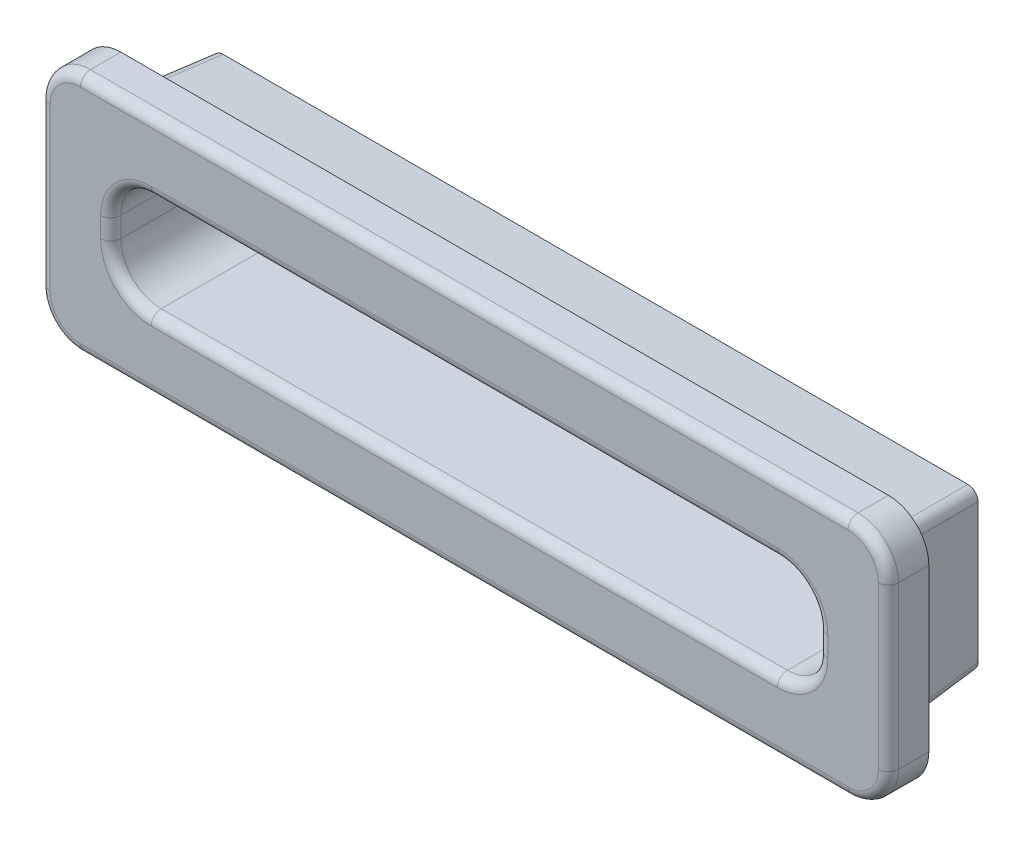
SolidWorks part; units mm, degrees
ref_plane "Front Plane" through (0, 0, 0) normal (0, 0, 1) x (1, 0, 0)
ref_plane "Top Plane" through (0, 0, 0) normal (0, 1, 0) x (1, 0, 0)
ref_plane "Right Plane" through (0, 0, 0) normal (1, 0, 0) x (0, 0, -1)
sketch "Sketch2" plane through (0, 0, 0) normal (0, 0, 1) x (1, 0, 0)
  line L1 (-35, 5) -> (35, 5)
  line L2 (-35, 5) -> (-35, -5)
  line L3 (-35, -5) -> (35, -5)
  line L4 (35, 5) -> (35, -5)
  line L5 (-35, 5) -> (35, -5) construction
  line L6 (-35, -5) -> (35, 5) construction
  line L7 (-42, 12) -> (42, 12)
  line L8 (-42, 12) -> (-42, -12)
  line L9 (-42, -12) -> (42, -12)
  line L10 (42, 12) -> (42, -12)
  line L11 (-42, 12) -> (42, -12) construction
  line L12 (-42, -12) -> (42, 12) construction
  point P0 (0, 0)
  point P5 (0, 0)
  dimension "D1" = 10
  dimension "D2" = 70
  dimension "D3" = 7
  dimension "D4" = 7
extrude "Boss-Extrude1" add sketch "Sketch2" along normal blind 4
sketch "Sketch3" plane through (0, 0, 0) normal (0, 0, 1) x (1, 0, 0)
  line L1 (35, 5) -> (-35, 5)
  line L2 (35, 5) -> (35, -5)
  line L3 (35, -5) -> (-35, -5)
  line L4 (-35, 5) -> (-35, -5)
  line L5 (35, 5) -> (-35, -5) construction
  line L6 (35, -5) -> (-35, 5) construction
  line L7 (38.5, 8.5) -> (-38.5, 8.5)
  line L8 (38.5, 8.5) -> (38.5, -8.5)
  line L9 (38.5, -8.5) -> (-38.5, -8.5)
  line L10 (-38.5, 8.5) -> (-38.5, -8.5)
  line L11 (38.5, 8.5) -> (-38.5, -8.5) construction
  line L12 (38.5, -8.5) -> (-38.5, 8.5) construction
  point P0 (0, 0)
  point P5 (0, 0)
  dimension "D1" = 3.5
  dimension "D2" = 3.5
extrude "Boss-Extrude2" add sketch "Sketch3" against normal blind 9
draft "Draft2" type of draft neutral plane draft angle 4 faces to draft 4 face at (0, 8.5, -4.5) face at (-38.5, 0, -4.5) face at (38.5, 0, -4.5) face at (0, -8.5, -4.5) neutral plane through (0, 0, 0) neutral plane normal (0, 0, -1) parameters "D1"=4
fillet "Fillet2" radius 4 8 edges at (-42, -12, 2) (-42, 12, 2) (42, 12, 2) (42, -12, 2) (35, 5, -2.5) (-35, 5, -2.5) (-35, -5, -2.5) (35, -5, -2.5)
fillet "Fillet1" radius 1 16 edges at (-35, 0, 4) (0, -5, 4) (35, 0, 4) (0, 5, 4) (0, -12, 4) (-42, 0, 4) (0, 12, 4) (42, 0, 4) (-33.8284, 3.8284, 4) (-33.8284, -3.8284, 4) (33.8284, -3.8284, 4) (33.8284, 3.8284, 4) (-40.8284, 10.8284, 4) (40.8284, 10.8284, 4) (40.8284, -10.8284, 4) (-40.8284, -10.8284, 4)
fillet "Fillet3" radius 1 4 edges at (38.1853, 8.1853, -4.5) (38.1853, -8.1853, -4.5) (-38.1853, 8.1853, -4.5) (-38.1853, -8.1853, -4.5)
